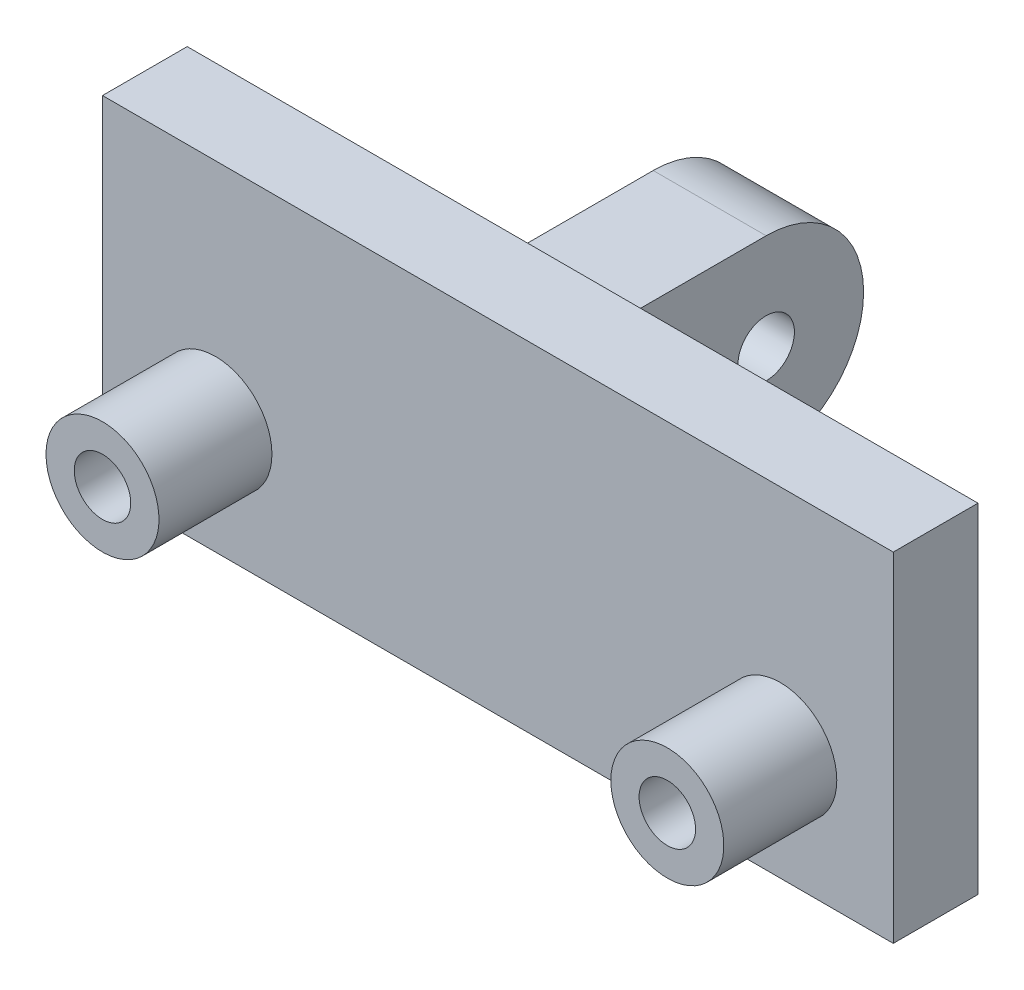
SolidWorks part; units mm, degrees
ref_plane "Alzado" through (0, 0, 0) normal (0, 0, 1) x (1, 0, 0)
ref_plane "Planta" through (0, 0, 0) normal (0, 1, 0) x (1, 0, 0)
ref_plane "Vista lateral" through (0, 0, 0) normal (1, 0, 0) x (0, 0, -1)
sketch "Croquis1" plane through (0, 0, 0) normal (0, 0, 1) x (1, 0, 0)
  line L1 (-30.4122, 13.3566) -> (-2.4122, 13.3566)
  line L2 (-30.4122, 13.3566) -> (-30.4122, 1.3566)
  line L3 (-30.4122, 1.3566) -> (-2.4122, 1.3566)
  line L4 (-2.4122, 13.3566) -> (-2.4122, 1.3566)
  dimension "D1" = 28
  dimension "D2" = 12
extrude "Saliente-Extruir1" add sketch "Croquis1" along normal blind 3
sketch "Croquis2" plane through (0, 0, 3) normal (0, 0, 1) x (1, 0, 0)
  line L1 (-2.4122, 1.3566) -> (-2.4122, 13.3566) construction
  line L2 (-30.4122, 1.3566) -> (-2.4122, 1.3566) construction
  circle A0 centre (-26.4122, 5.3566) radius 1
  circle A1 centre (-6.4122, 5.3566) radius 1
  dimension "D1" = 20
  dimension "D2" = 4
  dimension "D3" = 4
extrude "Cortar-Extruir1" cut sketch "Croquis2" against normal up to vertex (3 mm away)
sketch "Croquis3" plane through (0, 0, 0) normal (0, 0, -1) x (-1, 0, 0)
  line L0 (2.4122, 13.3566) -> (30.4122, 13.3566) construction
  line L1 (17.9122, 13.3566) -> (14.9122, 13.3566)
  line L2 (17.9122, 13.3566) -> (17.9122, 4.9645)
  line L3 (17.9122, 4.9645) -> (14.9122, 4.9645)
  line L4 (14.9122, 13.3566) -> (14.9122, 4.9645)
  line L5 (30.4122, 13.3566) -> (30.4122, 1.3566) construction
  dimension "D1" = 3
  dimension "D2" = 12.5
extrude "Saliente-Extruir2" add sketch "Croquis3" along normal blind 8
sketch "Croquis4" plane through (-17.9122, 0, 0) normal (-1, 0, 0) x (0, 0, 1)
  line L0 (-8, 4.9645) -> (-8, 13.3566) construction
  line L1 (-8, 13.3566) -> (0, 13.3566) construction
  circle A0 centre (-4.5, 9.8566) radius 1
  dimension "D1" = 3.5
  dimension "D2" = 3.5
extrude "Cortar-Extruir2" cut sketch "Croquis4" against normal up to vertex (3 mm away)
sketch "Croquis6" plane through (-17.9122, 0, 0) normal (-1, 0, 0) x (0, 0, 1)
  line L0 (-8, 13.3566) -> (-4.5, 13.3566)
  line L1 (-8, 13.3566) -> (-8, 6.3521)
  line L2 (-8, 4.9645) -> (-8, 13.3566) construction
  line L3 (-4.5, 6.4066) -> (0, 6.4066)
  line L4 (0, 4.9645) -> (0, 13.3566) construction
  line L5 (0, 6.4066) -> (0, 4.9645)
  line L6 (0, 4.9645) -> (-8, 4.9645)
  line L7 (-8, 4.9645) -> (-8, 6.3521)
  line L8 (-8, 13.3566) -> (0, 13.3566) construction
  line L9 (-4.5, 13.3566) -> (0, 13.3566)
  line L10 (0, 13.3566) -> (0, 13.3066)
  line L11 (0, 13.3066) -> (-4.5, 13.3066)
  arc A0 (-4.5, 6.4066) -> (-4.5, 13.3066) centre (-4.5, 9.8566) cw
extrude "Cortar-Extruir3" cut sketch "Croquis6" against normal blind 8
sketch "Croquis8" plane through (0, 0, 0) normal (0, 0, -1) x (-1, 0, 0)
  circle A0 centre (26.4122, 5.3566) radius 1
  circle A1 centre (6.4122, 5.3566) radius 1
  circle A2 centre (6.4122, 5.3566) radius 2
  circle A3 centre (26.4122, 5.3566) radius 2
extrude "Saliente-Extruir3" add sketch "Croquis8" against normal blind 7
sketch "Croquis11" plane through (-17.9122, 0, 0) normal (-1, 0, 0) x (0, 0, 1)
  line L0 (-4.5, 6.4066) -> (0, 6.4066)
  line L1 (0, 6.4066) -> (0, 13.3066)
  line L2 (0, 13.3066) -> (-4.5, 13.3066)
  arc A0 (-4.5, 6.4066) -> (-4.5, 13.3066) centre (-4.5, 9.8566) cw
  circle A1 centre (-4.5, 9.8566) radius 1
extrude "Saliente-Extruir4" add sketch "Croquis11" along normal blind 0.5
sketch "Croquis12" plane through (-14.9122, 0, 0) normal (1, 0, 0) x (0, 0, -1)
  line L0 (4.5, 13.3066) -> (0, 13.3066)
  line L1 (0, 13.3066) -> (0, 6.4066)
  line L2 (0, 6.4066) -> (4.5, 6.4066)
  arc A0 (4.5, 13.3066) -> (4.5, 6.4066) centre (4.5, 9.8566) cw
  circle A1 centre (4.5, 9.8566) radius 1
extrude "Saliente-Extruir5" add sketch "Croquis12" along normal blind 0.5
